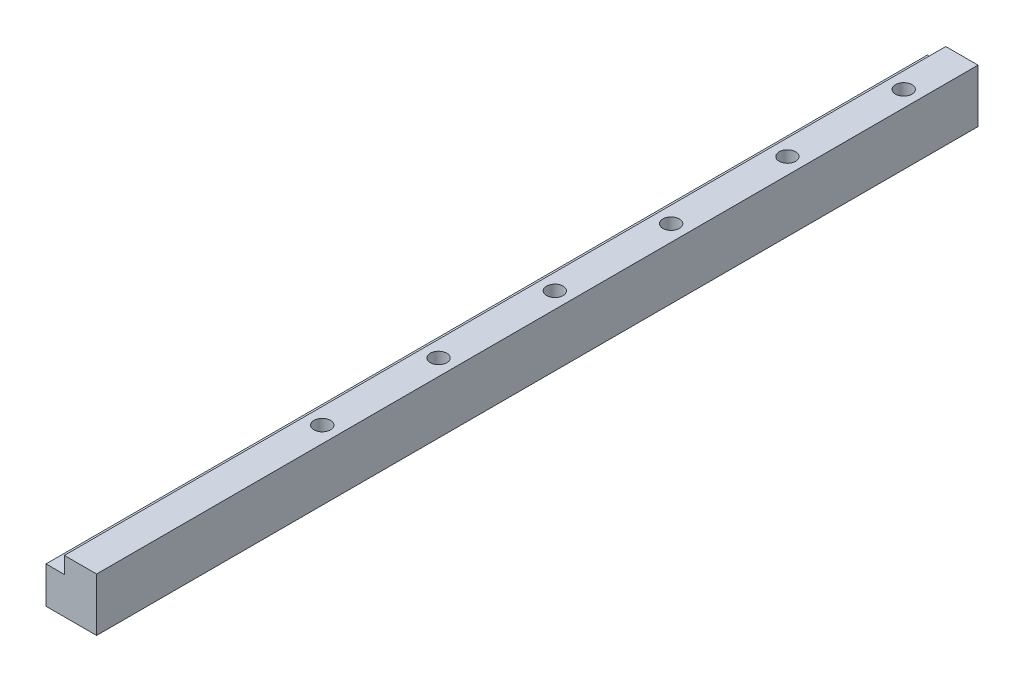
SolidWorks part; units mm, degrees
ref_plane "Plan de face" through (0, 0, 0) normal (0, 0, 1) x (1, 0, 0)
ref_plane "Plan de dessus" through (0, 0, 0) normal (0, 1, 0) x (1, 0, 0)
ref_plane "Plan de droite" through (0, 0, 0) normal (1, 0, 0) x (0, 0, -1)
sketch "Esquisse1" plane through (0, 0, 0) normal (0, 0, 1) x (1, 0, 0)
  line L0 (-13.7771, 10) -> (-8.7771, 10)
  line L1 (-8.7771, 10) -> (-8.7771, 14.5)
  line L2 (-8.7771, 14.5) -> (0, 14.5)
  line L3 (0, 14.5) -> (0, 0)
  line L4 (0, 0) -> (-13.7771, 0)
  line L5 (-13.7771, 0) -> (-13.7771, 10)
  dimension "D1" = 8.7771
  dimension "D2" = 14.5
  dimension "D3" = 13.7771
  dimension "D4" = 10
extrude "Boss.-Extru.1" add sketch "Esquisse1" along normal mid plane 200
hole_wizard "Diamètre du perçage Ø4.5 (4.5)1" positions "Esquisse2" profile "Esquisse3" hole size "Ø4.5" standard "Ansi Metric" end condition through all
sketch "Esquisse2" plane through (0, 14.5, 0) normal (0, 1, 0) x (1, 0, 0)
  line L0 (-4.3885, 100) -> (-4.3885, 68.3333) construction
  line L1 (0, 100) -> (-8.7771, 100) construction
  line L2 (-4.3885, 68.3333) -> (-4.3885, 36.6667) construction
  line L3 (-4.3885, 36.6667) -> (-4.3885, 5) construction
  line L4 (-4.3885, 5) -> (-4.3885, -26.6667) construction
  line L5 (-4.3885, -26.6667) -> (-4.3885, -58.3333) construction
  line L6 (-4.3885, -58.3333) -> (-4.3885, -90) construction
  point P16 (-4.3885, 84.1667)
  point P18 (-4.3885, 52.5)
  point P20 (-4.3885, 20.8333)
  point P22 (-4.3885, -10.8333)
  point P24 (-4.3885, -42.5)
  point P26 (-4.3885, -74.1667)
  dimension "D1" = 190
sketch "Esquisse3" plane through (-4.3885, 14.5, 74.1667) normal (1, 0, 0) x (0, 0, 1)
  line L0 (0, 0) -> (0, 14.5)
  line L1 (0, 14.5) -> (2.25, 14.5)
  line L2 (2.25, 14.5) -> (2.25, 0)
  line L5 (2.25, 0) -> (0, 0)
  line L11 (0, -6.35) -> (0, 107.95) construction
  dimension "Diamètre du perçage jusqu'au prochain" = 4.5
  dimension "Profondeur du perçage jusqu'au prochain" = 14.5
sketch "Esquisse4" plane through (0, 0, 100) normal (0, 0, 1) x (1, 0, 0)
  line L6 (-13.7771, 10) -> (-13.7771, 0)
  line L7 (-13.7771, 0) -> (0, 0)
  line L8 (0, 0) -> (0, 14.5)
  line L9 (0, 14.5) -> (-8.7771, 14.5)
  line L10 (-8.7771, 14.5) -> (-8.7771, 10)
  line L11 (-8.7771, 10) -> (-13.7771, 10)
  line L12 (-13.7771, 10) -> (-13.7771, 0)
  line L13 (-13.7771, 0) -> (0, 0)
  line L14 (0, 0) -> (0, 14.5)
  line L15 (0, 14.5) -> (-8.7771, 14.5)
  line L16 (-8.7771, 14.5) -> (-8.7771, 10)
  line L17 (-8.7771, 10) -> (-13.7771, 10)
  dimension "D1" = 0
extrude "Boss.-Extru.2" add sketch "Esquisse4" along normal blind 40
